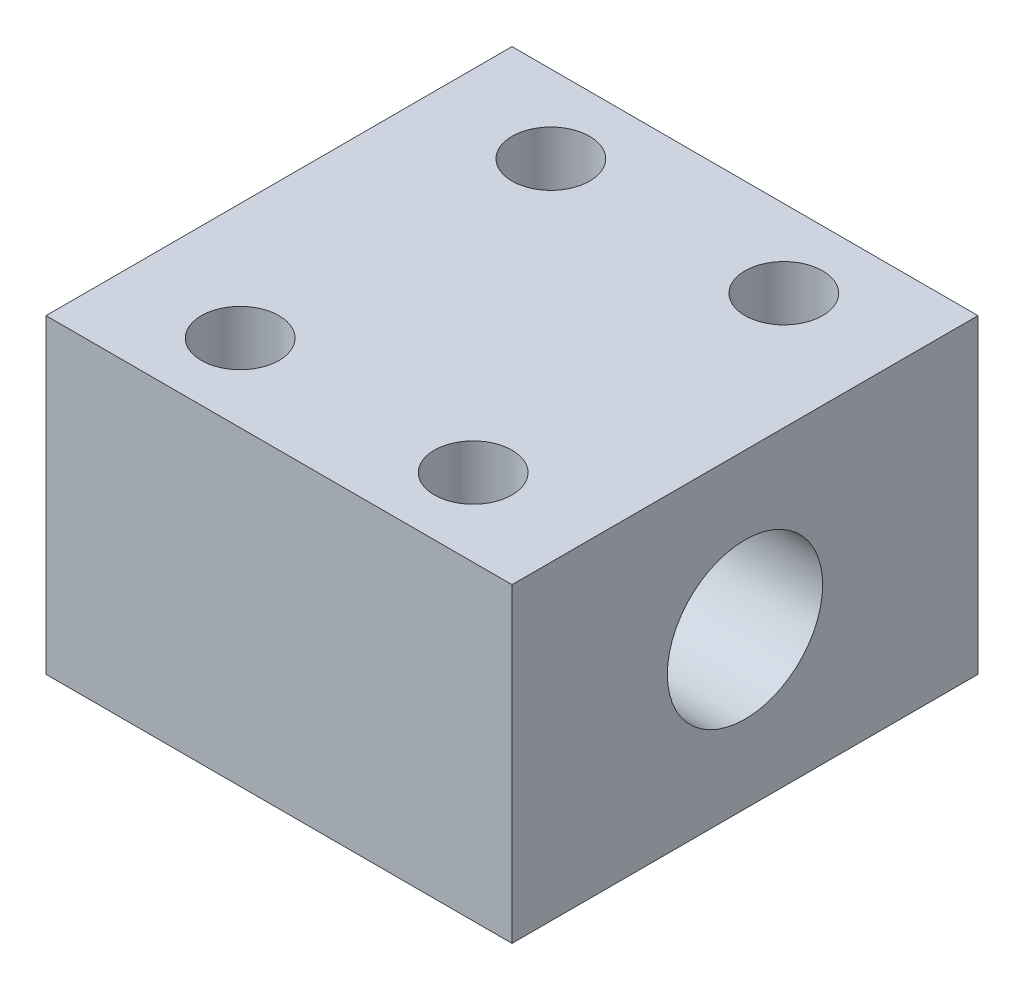
SolidWorks part; units mm, degrees
ref_plane "Front Plane" through (0, 0, 0) normal (0, 0, 1) x (1, 0, 0)
ref_plane "Top Plane" through (0, 0, 0) normal (0, 1, 0) x (1, 0, 0)
ref_plane "Right Plane" through (0, 0, 0) normal (1, 0, 0) x (0, 0, -1)
sketch "Sketch1" plane through (0, 0, 0) normal (0, 1, 0) x (1, 0, 0)
  line L0 (0, 23.746) -> (0, -28.4421) construction
  line L1 (-19.05, 19.05) -> (19.05, 19.05)
  line L2 (-19.05, 19.05) -> (-19.05, -19.05)
  line L3 (-19.05, -19.05) -> (19.05, -19.05)
  line L4 (19.05, 19.05) -> (19.05, -19.05)
  line L5 (-19.05, 19.05) -> (19.05, -19.05) construction
  line L6 (-19.05, -19.05) -> (19.05, 19.05) construction
  line L7 (-32.8723, 0) -> (41.2898, 0) construction
  circle A0 centre (-9.525, 12.7) radius 3.175
  circle A1 centre (9.525, 12.7) radius 3.175
  circle A2 centre (9.525, -12.7) radius 3.175
  circle A3 centre (-9.525, -12.7) radius 3.175
  point P1 (0, 0)
  dimension "D3" = 6.35
  dimension "D1" = 38.1
  dimension "D2" = 38.1
  dimension "D4" = 9.525
  dimension "D5" = 6.35
  dimension "D6" = 19.05
extrude "Boss-Extrude1" add sketch "Sketch1" along normal blind 25.4
sketch "Sketch2" plane through (19.05, 0, 0) normal (1, 0, 0) x (0, 0, -1)
  line L0 (-19.05, 25.4) -> (19.05, 25.4) construction
  line L1 (19.05, 25.4) -> (19.05, 0) construction
  circle A0 centre (0, 12.7) radius 6.35
  dimension "D1" = 12.7
  dimension "D2" = 12.7
  dimension "D3" = 19.05
extrude "Cut-Extrude1" cut sketch "Sketch2" against normal through all
